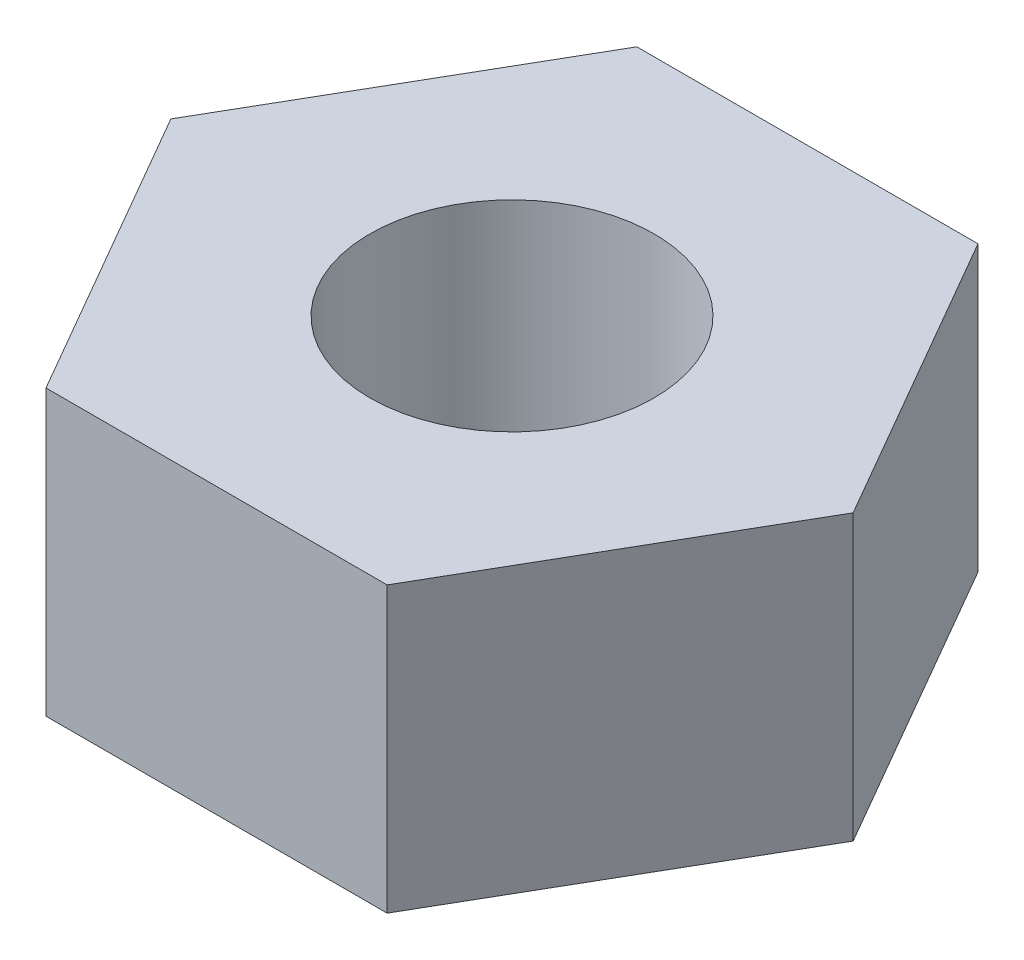
SolidWorks part; units mm, degrees
ref_plane "Front Plane" through (0, 0, 0) normal (0, 0, 1) x (1, 0, 0)
ref_plane "Top Plane" through (0, 0, 0) normal (0, 1, 0) x (1, 0, 0)
ref_plane "Right Plane" through (0, 0, 0) normal (1, 0, 0) x (0, 0, -1)
sketch "Sketch1" plane through (0, 0, 0) normal (0, 1, 0) x (1, 0, 0)
  line L1 (6, 10.3923) -> (-6, 10.3923)
  line L2 (-6, 10.3923) -> (-12, 0)
  line L3 (-12, 0) -> (-6, -10.3923)
  line L4 (-6, -10.3923) -> (6, -10.3923)
  line L5 (6, -10.3923) -> (12, 0)
  line L6 (12, 0) -> (6, 10.3923)
  circle A0 centre (0, 0) radius 10.3923 construction
  dimension "D1" = 12
extrude "Boss-Extrude1" add sketch "Sketch1" along normal blind 10
sketch "Sketch2" plane through (0, 10, 0) normal (0, 1, 0) x (1, 0, 0)
  circle A0 centre (0, 0) radius 5
  dimension "D1" = 10
extrude "Cut-Extrude1" cut sketch "Sketch2" against normal blind 10
